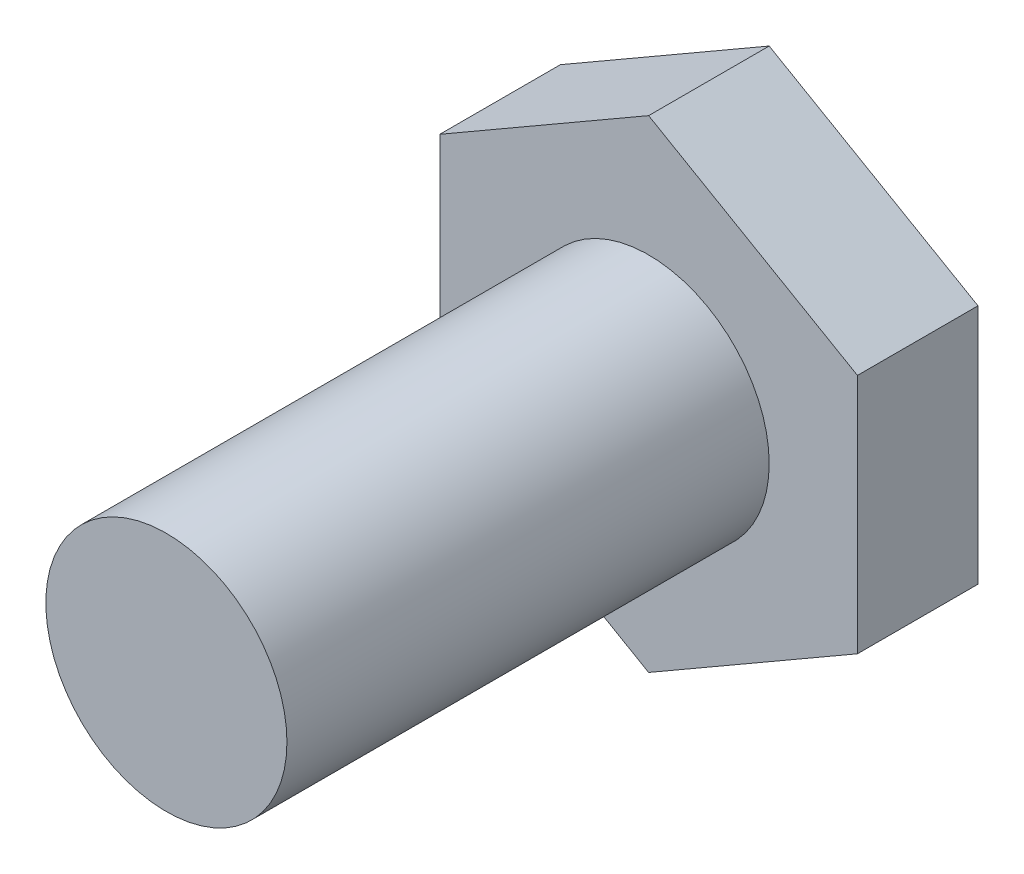
SolidWorks part; units mm, degrees
ref_plane "Plan de face" through (0, 0, 0) normal (0, 0, 1) x (1, 0, 0)
ref_plane "Plan de dessus" through (0, 0, 0) normal (0, 1, 0) x (1, 0, 0)
ref_plane "Plan de droite" through (0, 0, 0) normal (1, 0, 0) x (0, 0, -1)
sketch "Esquisse1" plane through (0, 0, 0) normal (0, 0, 1) x (1, 0, 0)
  circle A0 centre (0, 0) radius 2
  circle A1 centre (0, 0) radius 4
  dimension "D1" = 4
  dimension "D2" = 8
extrude "Boss.-Extru.1" add sketch "Esquisse1" along normal blind 8 contours A0
sketch "Esquisse2" plane through (0, 0, 0) normal (0, 0, -1) x (-1, 0, 0)
  line L0 (0, 0) -> (0, 4)
  line L2 (0, 4) -> (-3.4641, 2)
  line L3 (-3.4641, 2) -> (-3.4641, -2)
  line L4 (-3.4641, -2) -> (0, -4)
  line L5 (0, -4) -> (3.4641, -2)
  line L6 (3.4641, -2) -> (3.4641, 2)
  line L7 (3.4641, 2) -> (0, 4)
  circle A0 centre (0, 0) radius 3.4641 construction
  dimension "D1" = 4
extrude "Boss.-Extru.2" add sketch "Esquisse2" along normal blind 2
